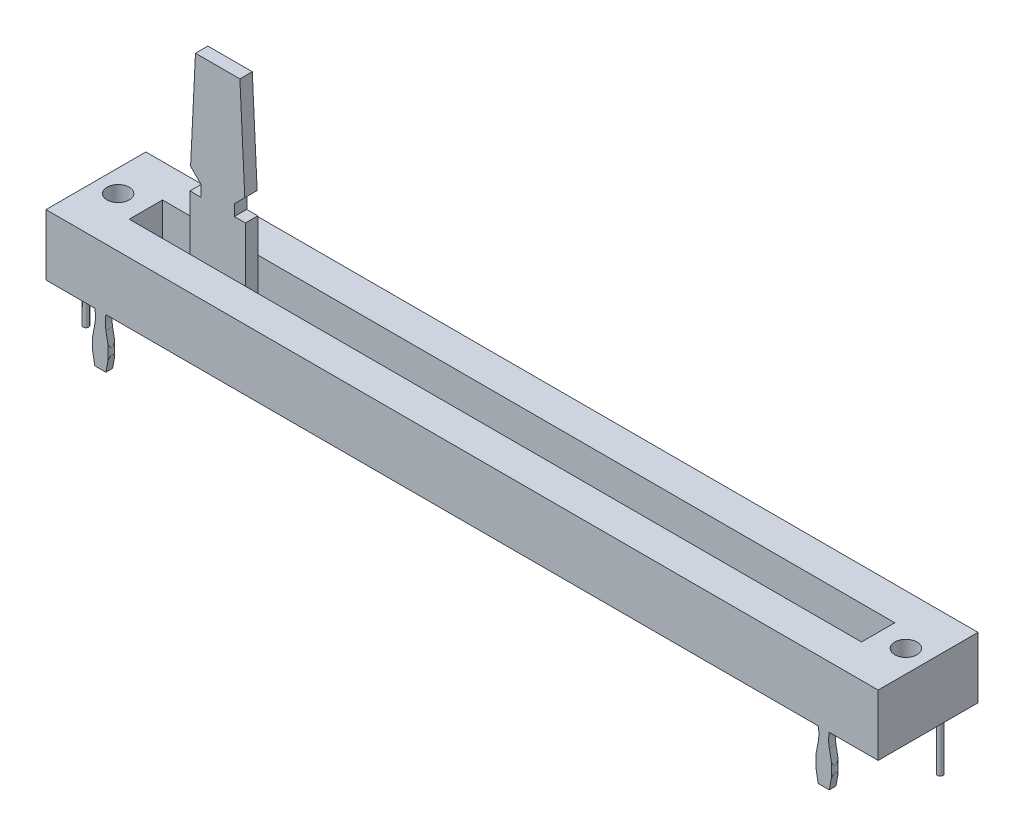
SolidWorks part; units mm, degrees
ref_plane "Front Plane" through (0, 0, 0) normal (0, 0, 1) x (1, 0, 0)
ref_plane "Top Plane" through (0, 0, 0) normal (0, 1, 0) x (1, 0, 0)
ref_plane "Right Plane" through (0, 0, 0) normal (1, 0, 0) x (0, 0, -1)
sketch "Sketch1" plane through (0, 0, 0) normal (0, 1, 0) x (1, 0, 0)
  line L1 (-37.5, -4.5) -> (37.5, -4.5)
  line L2 (-37.5, -4.5) -> (-37.5, 4.5)
  line L3 (-37.5, 4.5) -> (37.5, 4.5)
  line L4 (37.5, -4.5) -> (37.5, 4.5)
  line L5 (-37.5, -4.5) -> (37.5, 4.5) construction
  line L6 (-37.5, 4.5) -> (37.5, -4.5) construction
  line L7 (-33, 1.5) -> (33, 1.5)
  line L8 (-33, 1.5) -> (-33, -1.5)
  line L9 (-33, -1.5) -> (33, -1.5)
  line L10 (33, 1.5) -> (33, -1.5)
  line L11 (-33, 1.5) -> (33, -1.5) construction
  line L12 (-33, -1.5) -> (33, 1.5) construction
  circle A0 centre (-35.5, 0) radius 1
  circle A1 centre (35.5, 0) radius 1
  point P0 (0, 0)
  point P10 (0, 0)
  dimension "D4" = 2
  dimension "D5" = 2
  dimension "D1" = 75
  dimension "D2" = 2
  dimension "D3" = 2
  dimension "D6" = 9
  dimension "D7" = 3
  dimension "D8" = 66
extrude "Boss-Extrude1" add sketch "Sketch1" along normal blind 5.5
sketch "Sketch2" plane through (0, 0, 0) normal (0, 1, 0) x (1, 0, 0)
  line L1 (-28.4686, 0.5585) -> (-23.4686, 0.5585)
  line L2 (-28.4686, 0.5585) -> (-28.4686, -0.5585)
  line L3 (-28.4686, -0.5585) -> (-23.4686, -0.5585)
  line L4 (-23.4686, 0.5585) -> (-23.4686, -0.5585)
  line L5 (-28.4686, 0.5585) -> (-23.4686, -0.5585) construction
  line L6 (-28.4686, -0.5585) -> (-23.4686, 0.5585) construction
  point P0 (-25.9686, 0)
  dimension "D1" = 5
extrude "Boss-Extrude2" add sketch "Sketch2" along normal blind 20.5 separate body
sketch "Sketch4" plane through (0, 0, 0.5585) normal (0, 0, 1) x (1, 0, 0)
  line L0 (-25.9686, 20.5) -> (-25.9686, -0.6291) construction
  line L1 (-28.4686, 20.5) -> (-23.4686, 20.5) construction
  line L2 (-25.9686, 20.5) -> (-23.9667, 20.5)
  line L3 (-28.4686, 9.5028) -> (-28.6953, 10.25)
  line L4 (-28.6953, 10.25) -> (-28.6953, 20.7699)
  line L5 (-28.6953, 20.7699) -> (-23.1678, 20.7699)
  line L6 (-27.971, 20.5) -> (-25.9686, 20.5)
  line L7 (-24.464, 9.5028) -> (-24.464, 10.506)
  line L8 (-23.4686, 20.5) -> (-23.4686, 0) construction
  line L9 (-24.464, 10.506) -> (-23.5266, 11.4435)
  line L10 (-28.4686, 20.5) -> (-28.4686, 0) construction
  line L11 (-27.4648, 9.5028) -> (-27.4648, 10.506)
  line L12 (-23.5266, 11.4435) -> (-23.9667, 20.5)
  line L13 (-27.4648, 10.506) -> (-28.4103, 11.4514)
  line L14 (-28.4103, 11.4514) -> (-27.971, 20.5)
  line L15 (-28.4686, 9.5028) -> (-27.4648, 9.5028)
  line L16 (-23.1678, 20.7699) -> (-23.1678, 10.25)
  line L17 (-23.1678, 10.25) -> (-23.4686, 9.5028)
  line L18 (-23.4686, 9.5028) -> (-24.464, 9.5028)
extrude "Cut-Extrude1" cut sketch "Sketch4" against normal up to next (1.1169 mm away)
sketch "Sketch5" plane through (0, 0, 0) normal (0, -1, 0) x (1, 0, 0)
  line L0 (0, 0) -> (0, 16.5944) construction
  line L1 (0, 0) -> (-42.9618, 0) construction
  line L2 (-37.5, 4.5) -> (37.5, 4.5) construction
  line L3 (-33.2874, 3.9) -> (-31.9126, 3.9)
  line L5 (-33.2874, 4.5) -> (-31.9126, 4.5)
  line L7 (-33.2874, 3.9) -> (-31.9126, 4.5) construction
  line L8 (-33.2874, 4.5) -> (-31.9126, 3.9) construction
  line L10 (-32.0824, -4.5112) -> (-30.7176, -4.5112)
  line L12 (-32.0824, -3.8888) -> (-30.7176, -3.8888)
  line L14 (-32.0824, -4.5112) -> (-30.7176, -3.8888) construction
  line L15 (-32.0824, -3.8888) -> (-30.7176, -4.5112) construction
  line L16 (31.9126, 3.9) -> (33.2874, 3.9)
  line L18 (31.9126, 4.5) -> (33.2874, 4.5)
  line L20 (31.9126, 3.9) -> (33.2874, 4.5) construction
  line L21 (31.9126, 4.5) -> (33.2874, 3.9) construction
  line L22 (30.7176, -4.5112) -> (32.0824, -4.5112)
  line L24 (30.7176, -3.8888) -> (32.0824, -3.8888)
  line L26 (30.7176, -4.5112) -> (32.0824, -3.8888) construction
  line L27 (30.7176, -3.8888) -> (32.0824, -4.5112) construction
  arc A0 (-33.2874, 4.5) -> (-33.2874, 3.9) centre (-32.6, 4.2) ccw
  arc A1 (31.9126, 4.5) -> (31.9126, 3.9) centre (32.6, 4.2) ccw
  arc A2 (32.0824, -3.8888) -> (32.0824, -4.5112) centre (31.4, -4.2) cw
  arc A3 (-30.7176, -3.8888) -> (-30.7176, -4.5112) centre (-31.4, -4.2) cw
  arc A4 (33.2874, 3.9) -> (33.2874, 4.5) centre (32.6, 4.2) ccw
  arc A5 (30.7176, -4.5112) -> (30.7176, -3.8888) centre (31.4, -4.2) cw
  arc A6 (-31.9126, 3.9) -> (-31.9126, 4.5) centre (-32.6, 4.2) ccw
  arc A7 (-32.0824, -4.5112) -> (-32.0824, -3.8888) centre (-31.4, -4.2) cw
  circle A8 centre (-36.65, 1.75) radius 0.25
  circle A9 centre (-36.65, -1.75) radius 0.25
  circle A10 centre (36.85, -1.75) radius 0.25
  dimension "D3" = 1.5
  dimension "D4" = 1.5
  dimension "D5" = 31.4
  dimension "D9" = 0.5
  dimension "D1" = 65.2
  dimension "D2" = 32.6
  dimension "D6" = 62.8
  dimension "D7" = 4.2
  dimension "D8" = 4.2
  dimension "D10" = 36.65
  dimension "D11" = 73.5
  dimension "D12" = 1.75
  dimension "D13" = 1.75
  dimension "D14" = 1.75
extrude "Boss-Extrude3" add sketch "Sketch5" along normal blind 4.5
sketch "Sketch6" plane through (0, 0, 4.5) normal (0, 0, 1) x (1, 0, 0)
  line L0 (-37.5, 0) -> (-33.2874, 0) construction
  line L1 (-31.9126, -4.5) -> (-33.2874, -4.5) construction
  line L2 (-33.0993, -4.5) -> (-33.4023, -2.8518)
  line L3 (-33.4023, -2.8518) -> (-33.0993, -1.2359)
  line L4 (-33.0993, 0) -> (-33.4023, 0)
  line L5 (-33.4023, 0) -> (-33.651, -2.8518)
  line L6 (-33.651, -2.8518) -> (-33.4023, -4.5557)
  line L7 (-33.4023, -4.5557) -> (-33.0993, -4.5)
  line L8 (-32.6, -4.5) -> (-32.6, 0.6819) construction
  line L9 (-31.7977, -4.5557) -> (-32.1007, -4.5)
  line L10 (-31.549, -2.8518) -> (-31.7977, -4.5557)
  line L11 (-31.7977, 0) -> (-31.549, -2.8518)
  line L12 (-32.1007, 0) -> (-31.7977, 0)
  line L13 (-31.7977, -2.8518) -> (-32.1007, -1.2359)
  line L14 (-32.1007, -4.5) -> (-31.7977, -2.8518)
  line L15 (32.0987, -4.5036) -> (31.7958, -2.8554)
  line L16 (31.7958, -2.8554) -> (32.0987, -1.2395)
  line L17 (32.0987, -0.0036) -> (31.7958, -0.0036)
  line L18 (31.7958, -0.0036) -> (31.5471, -2.8554)
  line L19 (31.5471, -2.8554) -> (31.7958, -4.5593)
  line L20 (31.7958, -4.5593) -> (32.0987, -4.5036)
  line L21 (32.598, -4.5036) -> (32.598, 0.6783) construction
  line L22 (33.4003, -4.5593) -> (33.0974, -4.5036)
  line L23 (33.649, -2.8554) -> (33.4003, -4.5593)
  line L24 (33.4003, -0.0036) -> (33.649, -2.8554)
  line L25 (33.0974, -0.0036) -> (33.4003, -0.0036)
  line L26 (33.4003, -2.8554) -> (33.0974, -1.2395)
  line L27 (33.0974, -4.5036) -> (33.4003, -2.8554)
  arc A0 (-33.0993, -1.2359) -> (-33.0993, 0) centre (-36.3956, -0.6179) ccw
  arc A1 (-32.1007, -1.2359) -> (-32.1007, 0) centre (-28.8044, -0.6179) cw
  arc A2 (32.0987, -1.2395) -> (32.0987, -0.0036) centre (28.8025, -0.6216) ccw
  arc A3 (33.0974, -1.2395) -> (33.0974, -0.0036) centre (36.3936, -0.6216) cw
extrude "Cut-Extrude2" cut sketch "Sketch6" against normal up to next (0.6 mm away)
sketch "Sketch7" plane through (0, 0, -4.5112) normal (0, 0, -1) x (-1, 0, 0)
  line L0 (-31.9078, -4.5061) -> (-32.2107, -2.8579)
  line L1 (-32.2107, -2.8579) -> (-31.9078, -1.242)
  line L2 (-31.9078, -0.0061) -> (-32.2107, -0.0061)
  line L3 (-32.2107, -0.0061) -> (-32.4594, -2.8579)
  line L4 (-32.4594, -2.8579) -> (-32.2107, -4.5618)
  line L5 (-32.2107, -4.5618) -> (-31.9078, -4.5061)
  line L6 (-31.4085, -4.5061) -> (-31.4085, 0.6758) construction
  line L7 (-30.6062, -4.5618) -> (-30.9091, -4.5061)
  line L8 (-30.3575, -2.8579) -> (-30.6062, -4.5618)
  line L9 (-30.6062, -0.0061) -> (-30.3575, -2.8579)
  line L10 (-30.9091, -0.0061) -> (-30.6062, -0.0061)
  line L11 (-30.6062, -2.8579) -> (-30.9091, -1.242)
  line L12 (-30.9091, -4.5061) -> (-30.6062, -2.8579)
  line L13 (30.901, -4.5038) -> (30.598, -2.8555)
  line L14 (30.598, -2.8555) -> (30.901, -1.2396)
  line L15 (30.901, -0.0038) -> (30.598, -0.0038)
  line L16 (30.598, -0.0038) -> (30.3493, -2.8555)
  line L17 (30.3493, -2.8555) -> (30.598, -4.5594)
  line L18 (30.598, -4.5594) -> (30.901, -4.5038)
  line L19 (31.4003, -4.5038) -> (31.4003, 0.6781) construction
  line L20 (32.2026, -4.5594) -> (31.8996, -4.5038)
  line L21 (32.4512, -2.8555) -> (32.2026, -4.5594)
  line L22 (32.2026, -0.0038) -> (32.4512, -2.8555)
  line L23 (31.8996, -0.0038) -> (32.2026, -0.0038)
  line L24 (32.2026, -2.8555) -> (31.8996, -1.2396)
  line L25 (31.8996, -4.5038) -> (32.2026, -2.8555)
  arc A0 (-31.9078, -1.242) -> (-31.9078, -0.0061) centre (-35.204, -0.6241) ccw
  arc A1 (-30.9091, -1.242) -> (-30.9091, -0.0061) centre (-27.6129, -0.6241) cw
  arc A2 (30.901, -1.2396) -> (30.901, -0.0038) centre (27.6047, -0.6217) ccw
  arc A3 (31.8996, -1.2396) -> (31.8996, -0.0038) centre (35.1959, -0.6217) cw
extrude "Cut-Extrude3" cut sketch "Sketch7" against normal up to next (8.4112 mm away)
sketch "Sketch8" plane through (0, 0, 0) normal (0, -1, 0) x (1, 0, 0)
  line L1 (-37.5, 4.5) -> (37.5, 4.5)
  line L2 (-37.5, 4.5) -> (-37.5, -4.5)
  line L3 (-37.5, -4.5) -> (37.5, -4.5)
  line L4 (37.5, 4.5) -> (37.5, -4.5)
extrude "Boss-Extrude4" add sketch "Sketch8" against normal blind 1
